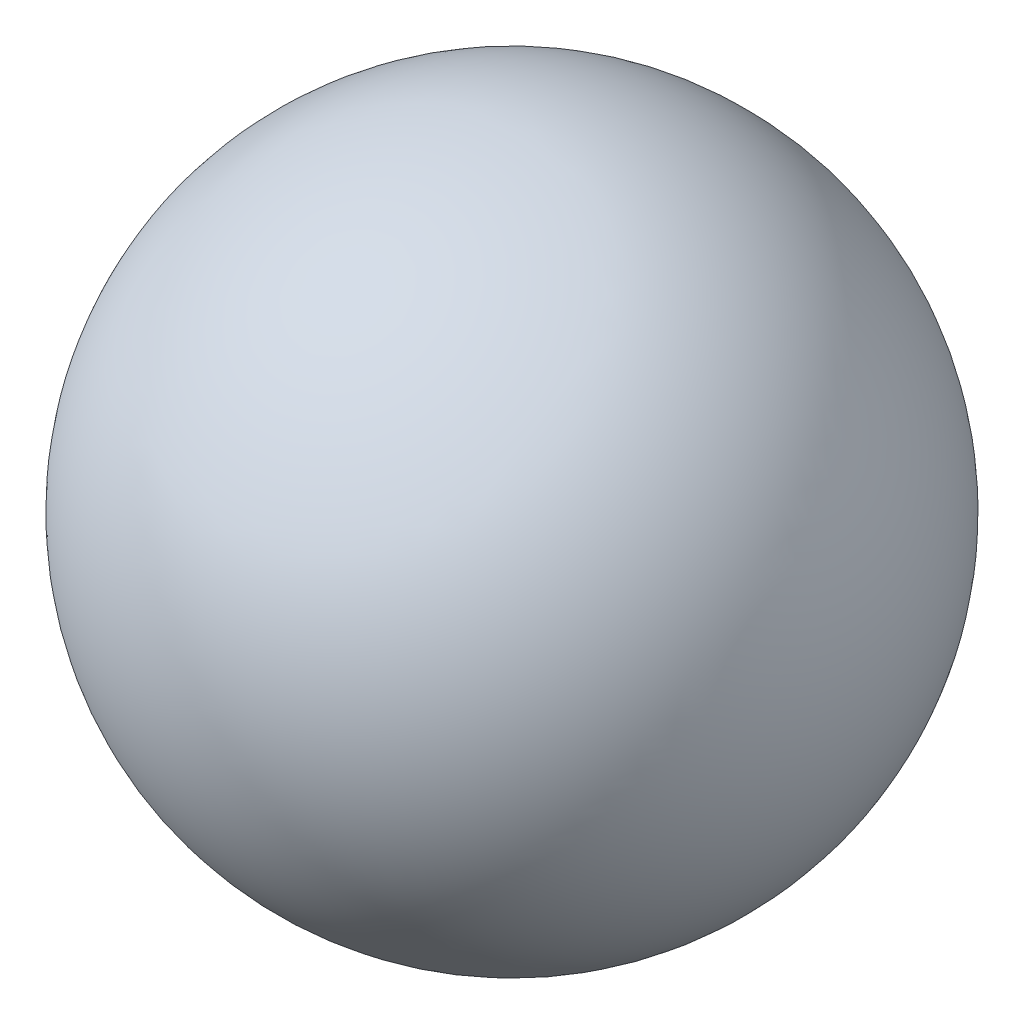
SolidWorks part; units mm, degrees
ref_plane "Face" through (0, 0, 0) normal (0, 0, 1) x (1, 0, 0)
ref_plane "Dessus" through (0, 0, 0) normal (0, 1, 0) x (1, 0, 0)
ref_plane "Droite" through (0, 0, 0) normal (1, 0, 0) x (0, 0, -1)
sketch "Esquisse1" plane through (0, 0, 0) normal (0, 0, 1) x (1, 0, 0)
  line L0 (-42.0818, 0) -> (58.9717, 0) construction
  line L1 (-4, 0) -> (4, 0)
  arc A0 (4, 0) -> (-4, 0) centre (0, 0) ccw
  dimension "D1" = 8
revolve "Révolution1" add sketch "Esquisse1" angle 360 about L0
